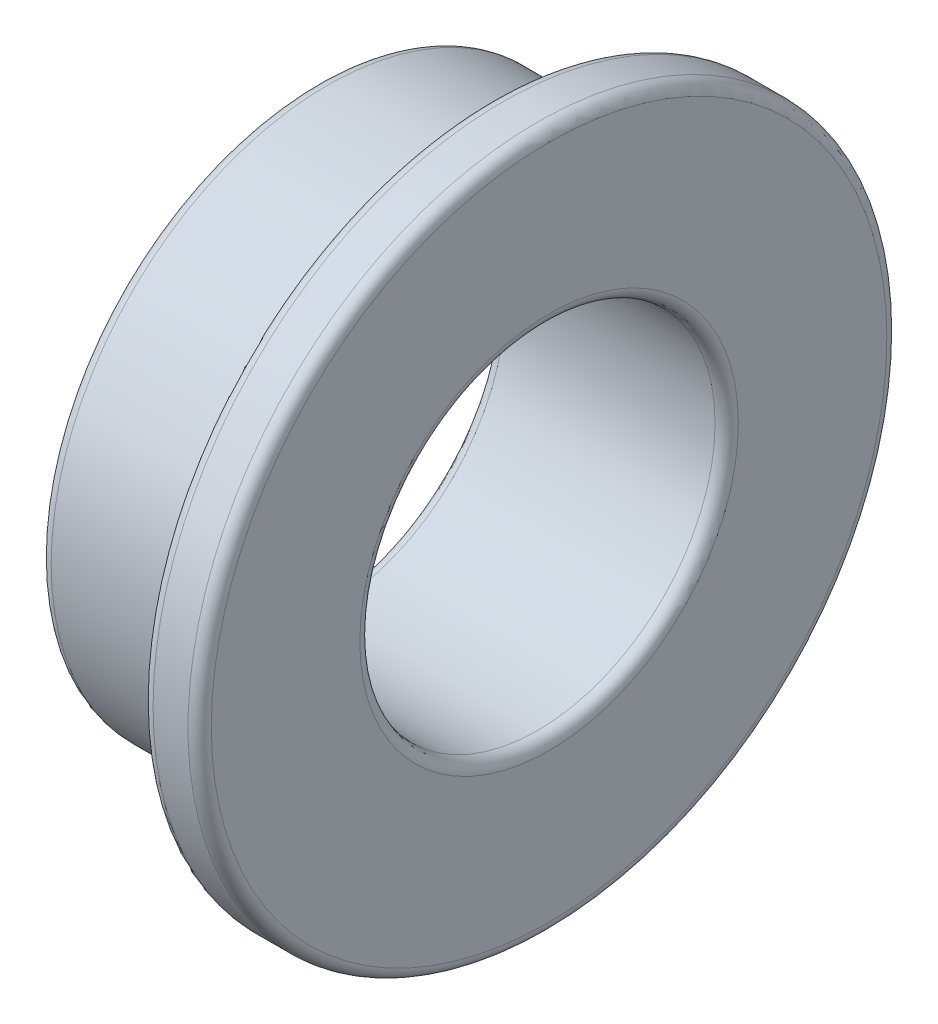
SolidWorks part; units mm, degrees
ref_plane "Front Plane" through (0, 0, 0) normal (0, 0, 1) x (1, 0, 0)
ref_plane "Top Plane" through (0, 0, 0) normal (0, 1, 0) x (1, 0, 0)
ref_plane "Right Plane" through (0, 0, 0) normal (1, 0, 0) x (0, 0, -1)
sketch "Sketch1" plane through (0, 0, 0) normal (0, 0, 1) x (1, 0, 0)
  line L0 (0, 0) -> (-8.0549, 0) construction
  line L1 (-4, 0) -> (-4, 4.75)
  line L2 (-4, 4.75) -> (-1, 4.75)
  line L3 (-1, 4.75) -> (-1, 6)
  line L4 (-1, 6) -> (0, 6)
  line L5 (0, 6) -> (0, 0)
  line L6 (0, 0) -> (-4, 0)
  dimension "D1" = 12
  dimension "D2" = 1
  dimension "D3" = 3
  dimension "D4" = 9.5
revolve "Revolve1" add sketch "Sketch1" angle 360 about L0
sketch "Sketch2" plane through (0, 0, 0) normal (1, 0, 0) x (0, 0, -1)
  circle A1 centre (0, 0) radius 3.05
  dimension "D1" = 6.1
extrude "Cut-Extrude1" cut sketch "Sketch2" against normal up to next
fillet "Fillet1" radius 0.2 6 edges at (0, 0, -6) (-1, 0, -6) (-1, 0, -4.75) (-4, 0, -4.75) (0, 0, -3.05) (-4, 0, 3.05)
